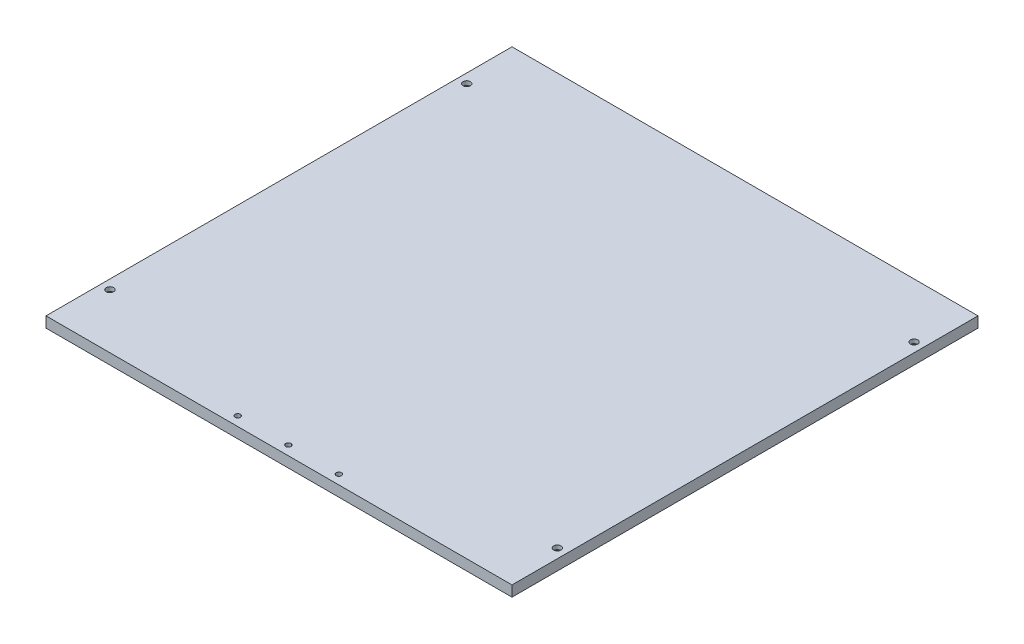
SolidWorks part; units mm, degrees
ref_plane "Front Plane" through (0, 0, 0) normal (0, 0, 1) x (1, 0, 0)
ref_plane "Top Plane" through (0, 0, 0) normal (0, 1, 0) x (1, 0, 0)
ref_plane "Right Plane" through (0, 0, 0) normal (1, 0, 0) x (0, 0, -1)
sketch "PlateSketch2" plane through (0, 0, 0) normal (0, 1, 0) x (1, 0, 0)
  line L1 (0, 0) -> (350, 0)
  line L2 (0, 0) -> (0, 350)
  line L3 (0, 350) -> (350, 350)
  line L4 (350, 0) -> (350, 350)
  circle A0 centre (7, 309) radius 2
  circle A1 centre (343, 309) radius 2
  circle A2 centre (137, 7) radius 2
  circle A3 centre (175, 7) radius 2
  circle A4 centre (213, 7) radius 2
  circle A5 centre (7, 41) radius 2
  circle A6 centre (343, 41) radius 2
  dimension "D5" = 4
  dimension "D10" = 4
  dimension "D1" = 350
  dimension "D2" = 350
  dimension "D3" = 7
  dimension "D4" = 7
  dimension "D6" = 41
  dimension "D7" = 38
  dimension "D8" = 38
  dimension "D9" = 175
  dimension "D11" = 7
  dimension "D12" = 41
extrude "Boss-Extrude1" add sketch "PlateSketch2" along normal blind 8
sketch "BoreSketch1" plane through (0, 8, 0) normal (0, 1, 0) x (1, 0, 0)
  circle A0 centre (7, 309) radius 2.75
  circle A1 centre (343, 309) radius 2.75
  circle A4 centre (7, 309) radius 2 construction
  circle A5 centre (343, 309) radius 2 construction
  circle A6 centre (7, 41) radius 2.75
  circle A7 centre (343, 41) radius 2.75
  dimension "D1" = 5.5
extrude "BoreCut-Extrude1" cut sketch "BoreSketch1" against normal blind 3
equation "\"BuildPlateStandoffHolesDistanceFromLeftOrRightSide\"= 7mm"
equation "\"BuildPlateStandoffHolesDistanceFromBackSide\"= 41mm"
equation "\"BedSpringHoleSize\" = \"M4HoleDiameter\""
equation "\"BuildPlateWidth\"= 350mm'Spec"
equation "\"BuildPlateLength\"= 350mm'Spec"
equation "\"D5@PlateSketch2\" = \"BedSpringHoleSize\""
equation "\"D10@PlateSketch2\" = \"BedSpringHoleSize\""
equation "\"BuildPlateBoreDiameter\"= \"M4BoreDiameter\"'Spec"
equation "\"D1@BoreSketch1\" = \"BuildPlateBoreDiameter\""
equation "\"BuildPlateBoreDepth\"= 3mm'Spec"
equation "\"D1@BoreCut-Extrude1\" = \"BuildPlateBoreDepth\""
equation "\"BuildPlateDepth\"= 8mm'Spec"
equation "\"D1@Boss-Extrude1\"=\"BuildPlateDepth\""
equation "\"D1@PlateSketch2\"= \"BuildPlateLength\""
equation "\"D2@PlateSketch2\"=\"BuildPlateWidth\""
equation "\"D9@PlateSketch2\"=\"BuildPlateWidth\"/2"
equation "\"BuildPlateFlankingHoles\"= 38mm"
equation "\"D7@PlateSketch2\"=\"BuildPlateFlankingHoles\""
equation "\"D6@PlateSketch2\"=\"BuildPlateStandoffHolesDistanceFromBackSide\""
equation "\"D3@PlateSketch2\"=\"BuildPlateStandoffHolesDistanceFromLeftOrRightSide\""
equation "\"D4@PlateSketch2\"=\"BuildPlateStandoffHolesDistanceFromLeftOrRightSide\""
equation "\"BuildPlateStandoffHolesDistanceFromFront\"= 7mm"
equation "\"D11@PlateSketch2\"=\"BuildPlateStandoffHolesDistanceFromFront\""
equation "\"D12@PlateSketch2\"=\"BuildPlateStandoffHolesDistanceFromBackSide\""
equation "\"M4HoleDiameter\"= 4mm"
equation "\"M4FlatHeadBoreDepth\"= .65mm"
equation "\"M4BoreDiameter\"= 5.5mm"
